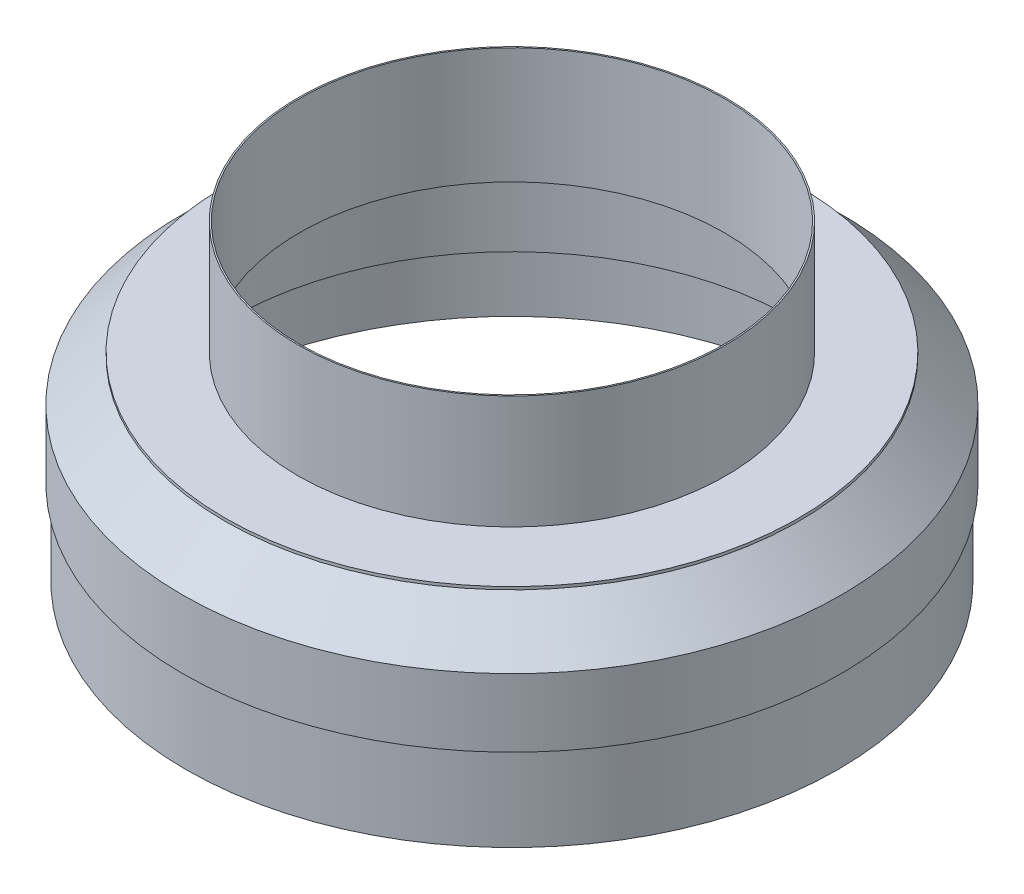
SolidWorks part; units mm, degrees
ref_plane "Спереди" through (0, 0, 0) normal (0, 0, 1) x (1, 0, 0)
ref_plane "Сверху" through (0, 0, 0) normal (0, 1, 0) x (1, 0, 0)
ref_plane "Справа" through (0, 0, 0) normal (1, 0, 0) x (0, 0, -1)
sketch "Эскиз1" plane through (0, 0, 0) normal (0, 1, 0) x (1, 0, 0)
  circle A0 centre (0, 0) radius 232.5
  circle A1 centre (0, 0) radius 200
  dimension "D1" = 465
  dimension "D2" = 400
extrude "Вытянуть1" add sketch "Эскиз1" along normal blind 78
sketch "Эскиз2" plane through (0, 78, 0) normal (0, 1, 0) x (1, 0, 0)
  circle A0 centre (0, 0) radius 150
  circle A1 centre (0, 0) radius 151
  dimension "D1" = 302
  dimension "D2" = 300
extrude "Вытянуть2" add sketch "Эскиз2" along normal blind 82
chamfer "Фаска1" distance 30 angle 45 1 edges at (0, 78, 232.5)
sketch "Эскиз4" plane through (0, 78, 0) normal (0, 1, 0) x (1, 0, 0)
  circle A0 centre (0, 0) radius 202.5
  circle A1 centre (0, 0) radius 202.5 construction
  circle A2 centre (0, 0) radius 150
  circle A3 centre (0, 0) radius 150 construction
extrude "Бобышка-Вытянуть1" add sketch "Эскиз4" along normal blind 2
sketch "Эскиз5" plane through (0, 0, 0) normal (0, -1, 0) x (1, 0, 0)
  circle A0 centre (0, 0) radius 229
  circle A1 centre (0, 0) radius 230
  dimension "D1" = 460
  dimension "D2" = 1
extrude "Бобышка-Вытянуть2" add sketch "Эскиз5" along normal blind 60
